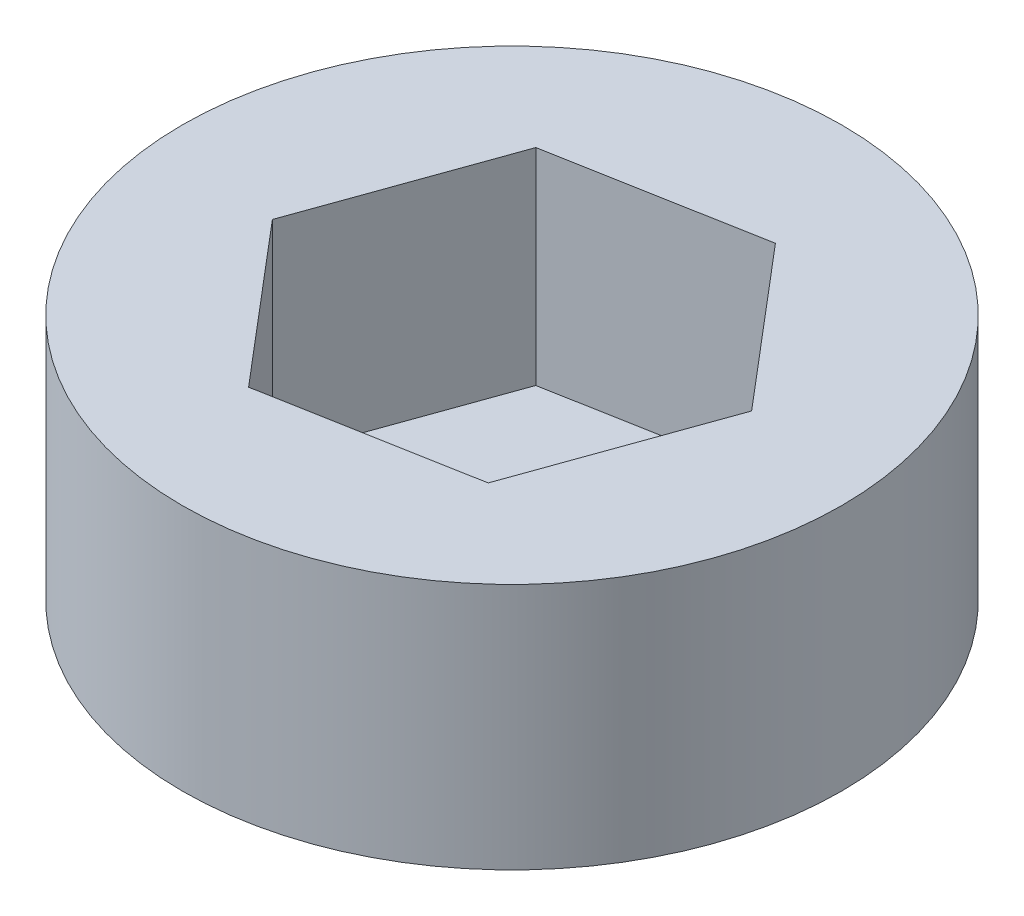
SolidWorks part; units mm, degrees
ref_plane "Front Plane" through (0, 0, 0) normal (0, 0, 1) x (1, 0, 0)
ref_plane "Top Plane" through (0, 0, 0) normal (0, 1, 0) x (1, 0, 0)
ref_plane "Right Plane" through (0, 0, 0) normal (1, 0, 0) x (0, 0, -1)
sketch "Sketch1" plane through (0, 0, 0) normal (0, 1, 0) x (1, 0, 0)
  circle A0 centre (0, 0) radius 10.16
extrude "Boss-Extrude1" add sketch "Sketch1" along normal blind 7.62
sketch "Sketch2" plane through (0, 7.62, 0) normal (0, 1, 0) x (1, 0, 0)
  circle A1 centre (0, 0) radius 1.5875
extrude "Cut-Extrude4" cut sketch "Sketch2" against normal through all
sketch "Sketch5" plane through (0, 7.62, 0) normal (0, 1, 0) x (1, 0, 0)
  line L1 (6.2474, 1.1371) -> (2.1389, 5.9789)
  line L2 (2.1389, 5.9789) -> (-4.1084, 4.8418)
  line L3 (-4.1084, 4.8418) -> (-6.2474, -1.1371)
  line L4 (-6.2474, -1.1371) -> (-2.1389, -5.9789)
  line L5 (-2.1389, -5.9789) -> (4.1084, -4.8418)
  line L6 (4.1084, -4.8418) -> (6.2474, 1.1371)
  circle A0 centre (0, 0) radius 5.4993 construction
extrude "Cut-Extrude5" cut sketch "Sketch5" against normal blind 6.35
